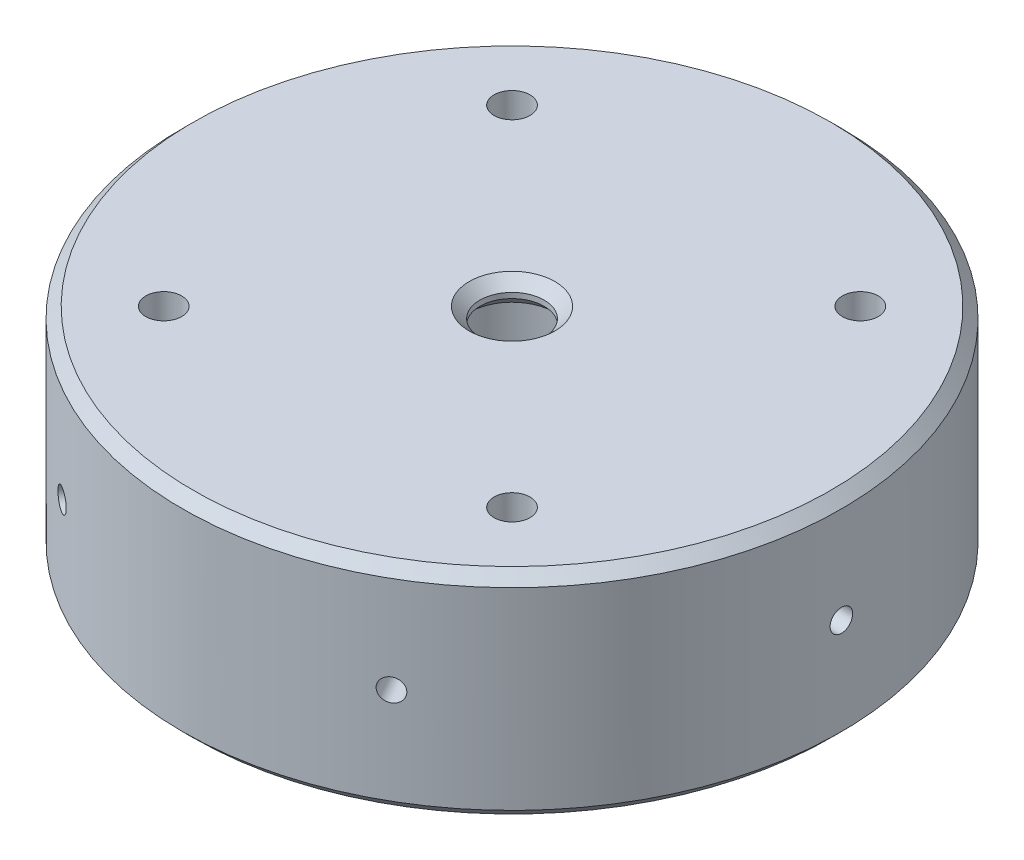
SolidWorks part; units mm, degrees
ref_plane "Front Plane" through (0, 0, 0) normal (0, 0, 1) x (1, 0, 0)
ref_plane "Top Plane" through (0, 0, 0) normal (0, 1, 0) x (1, 0, 0)
ref_plane "Right Plane" through (0, 0, 0) normal (1, 0, 0) x (0, 0, -1)
sketch "Sketch1" plane through (0, 0, 0) normal (1, 0, 0) x (0, 0, -1)
  line L0 (-24, 0) -> (0, 0) construction
  line L1 (0, 0) -> (0, 48.7156) construction
  line L2 (-24, 0) -> (-61.5, 0)
  line L3 (-61.5, 0) -> (-61.5, 40)
  line L4 (-61.5, 40) -> (-6, 40)
  line L5 (-6, 40) -> (-6, 35)
  line L6 (-6, 35) -> (-13, 35)
  line L8 (-24, 0) -> (-24, 7.5)
  line L9 (-24, 7.5) -> (-13, 7.5)
  line L10 (-13, 7.5) -> (-13, 35)
  point P10 (-6, 37.5)
  dimension "D1" = 123
  dimension "D2" = 12
  dimension "D3" = 48
  dimension "D4" = 26
  dimension "D5" = 35
  dimension "D6" = 5
  dimension "D7" = 27.5
revolve "Revolve1" add sketch "Sketch1" angle 360 about L1
ref_plane "Plane1" through (61.5, 0, 0) normal (1, 0, 0) x (0, 0, -1)
sketch "Sketch2" plane through (0, 40, 0) normal (0, 1, 0) x (1, 0, 0)
  line L1 (-32.5, -32.5) -> (32.5, -32.5) construction
  line L2 (-32.5, -32.5) -> (-32.5, 32.5) construction
  line L3 (-32.5, 32.5) -> (32.5, 32.5) construction
  line L4 (32.5, -32.5) -> (32.5, 32.5) construction
  line L5 (-32.5, -32.5) -> (32.5, 32.5) construction
  line L6 (-32.5, 32.5) -> (32.5, -32.5) construction
  circle A0 centre (0, 0) radius 45.9619 construction
  circle A1 centre (-32.5, 32.5) radius 3.35
  dimension "D1" = 65
  dimension "D2" = 6.7
extrude "Cut-Extrude1" cut sketch "Sketch2" against normal blind 25
cosmetic thread "Cosmetic Thread1" parameters "D2"=8
pattern_circular "CirPattern1" count 4 over 360 about axis through (0, 0, 0) along (0, 1, 0) of "Cut-Extrude1"
cosmetic thread "Cosmetic Thread2" parameters "D2"=8
cosmetic thread "Cosmetic Thread3" parameters "D2"=8
cosmetic thread "Cosmetic Thread4" parameters "D2"=8
sketch "Sketch5" plane through (0, 0, 0) normal (0, -1, 0) x (1, 0, 0)
  circle A0 centre (0, 0) radius 29
  circle A1 centre (0, 0) radius 53.5
  circle A2 centre (0, 0) radius 61.5 construction
  circle A3 centre (0, 0) radius 24 construction
  dimension "D1" = 8
  dimension "D2" = 5
extrude "Cut-Extrude4" cut sketch "Sketch5" against normal offset from surface (28 mm away) 12 up to face at (29.15, 40, -32.5)
ref_plane "Plane4outerHoles" through (61.5, 0, 0) normal (1, 0, 0) x (0, 0, -1)
sketch "Sketch6" plane through (61.5, 0, 0) normal (1, 0, 0) x (0, 0, -1)
  line L0 (-61.5, 40) -> (-61.5, 0) construction
  circle A0 centre (0, 20) radius 2.1
  point P5 (-61.5, 20)
  dimension "D1" = 4.2
extrude "Cut-Extrude5" cut sketch "Sketch6" against normal up to next
cosmetic thread "Cosmetic Thread5" parameters "D2"=5
pattern_circular "CirPattern2" count 6 over 360 about axis through (0, 40, 0) along (0, -1, 0) of "Cut-Extrude5"
cosmetic thread "Cosmetic Thread6" parameters "D2"=5
cosmetic thread "Cosmetic Thread7" parameters "D2"=5
cosmetic thread "Cosmetic Thread8" parameters "D2"=5
cosmetic thread "Cosmetic Thread9" parameters "D2"=5
cosmetic thread "Cosmetic Thread10" parameters "D2"=5
chamfer "Chamfer1" distance 2 angle 45 8 edges at (0, 0, -61.5) (0, 0, -53.5) (0, 0, -29) (0, 0, -24) (0, 40, -61.5) (0, 7.5, -13) (0, 35, -6) (0, 40, -6)
fillet "Fillet2" radius 1 3 edges at (0, 35, -13) (0, 7.5, -24) (0, 28, -53.5)
fillet "Fillet3" radius 5 1 edges at (0, 28, -29)
equation "\"D4@Sketch1\"=\"D3@Sketch1\"/2+2"
